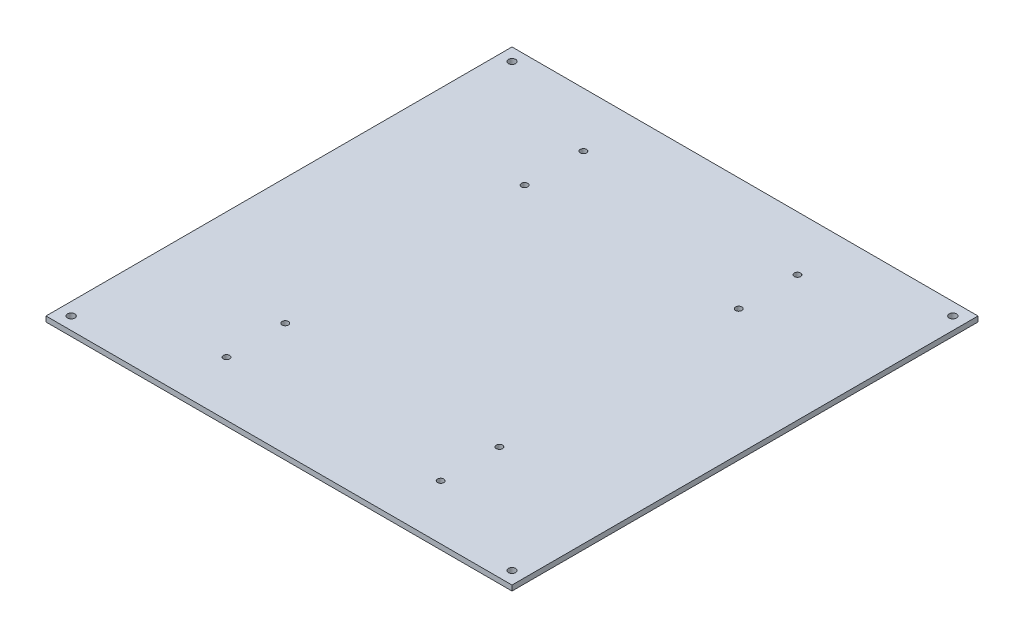
SolidWorks part; units mm, degrees
ref_plane "前视基准面" through (0, 0, 0) normal (0, 0, 1) x (1, 0, 0)
ref_plane "上视基准面" through (0, 0, 0) normal (0, 1, 0) x (1, 0, 0)
ref_plane "右视基准面" through (0, 0, 0) normal (1, 0, 0) x (0, 0, -1)
sketch "草图1" plane through (0, 0, 0) normal (0, 1, 0) x (1, 0, 0)
  line L1 (0, 0) -> (222, 0)
  line L2 (0, 0) -> (0, 222)
  line L3 (0, 222) -> (222, 222)
  line L4 (222, 0) -> (222, 222)
  line L5 (0, 0) -> (222, 222) construction
  line L6 (0, 222) -> (222, 0) construction
  line L7 (6, 216) -> (216, 216) construction
  line L8 (6, 216) -> (6, 6) construction
  line L9 (6, 6) -> (216, 6) construction
  line L10 (216, 216) -> (216, 6) construction
  line L11 (111, 6) -> (111, 216) construction
  line L12 (6, 111) -> (216, 111) construction
  circle A0 centre (6, 6) radius 1.75
  circle A1 centre (216, 6) radius 1.75
  circle A2 centre (216, 216) radius 1.75
  circle A3 centre (6, 216) radius 1.75
  point P4 (111, 111)
  point P6 (111, 111)
  dimension "D4" = 3.5
  dimension "D1" = 222
  dimension "D2" = 222
  dimension "D3" = 210
extrude "凸台-拉伸1" add sketch "草图1" along normal blind 2.5
sketch "草图2" plane through (0, 0, 0) normal (0, -1, 0) x (1, 0, 0)
  line L0 (60, 0) -> (60, -222) construction
  line L1 (0, 0) -> (222, 0) construction
  line L2 (222, -222) -> (0, -222) construction
  line L3 (0, -222) -> (0, 0) construction
  line L4 (111, 0) -> (111, -222) construction
  line L5 (0, -111) -> (222, -111) construction
  line L6 (222, 0) -> (222, -222) construction
  circle A0 centre (60, -26) radius 1.5
  circle A1 centre (60, -54) radius 1.5
  circle A2 centre (60, -168) radius 1.5
  circle A3 centre (60, -196) radius 1.5
  circle A4 centre (162, -196) radius 1.5
  circle A5 centre (162, -168) radius 1.5
  circle A6 centre (162, -54) radius 1.5
  circle A7 centre (162, -26) radius 1.5
  dimension "D1" = 3
  dimension "D2" = 3
  dimension "D3" = 28
  dimension "D4" = 26
  dimension "D5" = 60
extrude "切除-拉伸1" cut sketch "草图2" against normal through all
